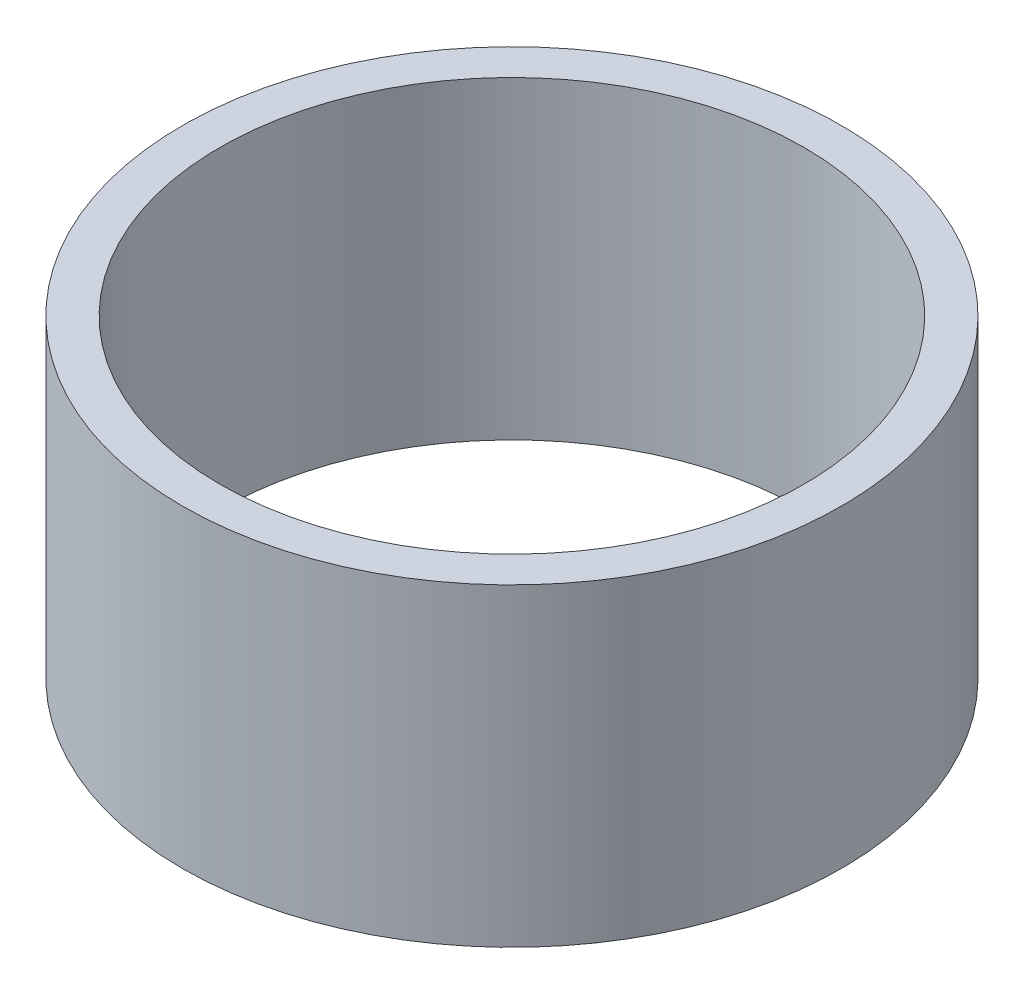
SolidWorks part; units mm, degrees
ref_plane "Front" through (0, 0, 0) normal (0, 0, 1) x (1, 0, 0)
ref_plane "Top" through (0, 0, 0) normal (0, 1, 0) x (1, 0, 0)
ref_plane "Right" through (0, 0, 0) normal (1, 0, 0) x (0, 0, -1)
sketch "Çizim1" plane through (0, 0, 0) normal (0, 1, 0) x (1, 0, 0)
  circle A0 centre (0, 0) radius 52.5
  circle A1 centre (0, 0) radius 46.5
  dimension "D1" = 105
  dimension "D2" = 6
extrude "Yükseklik-Ekstrüzyon1" add sketch "Çizim1" along normal blind 50
